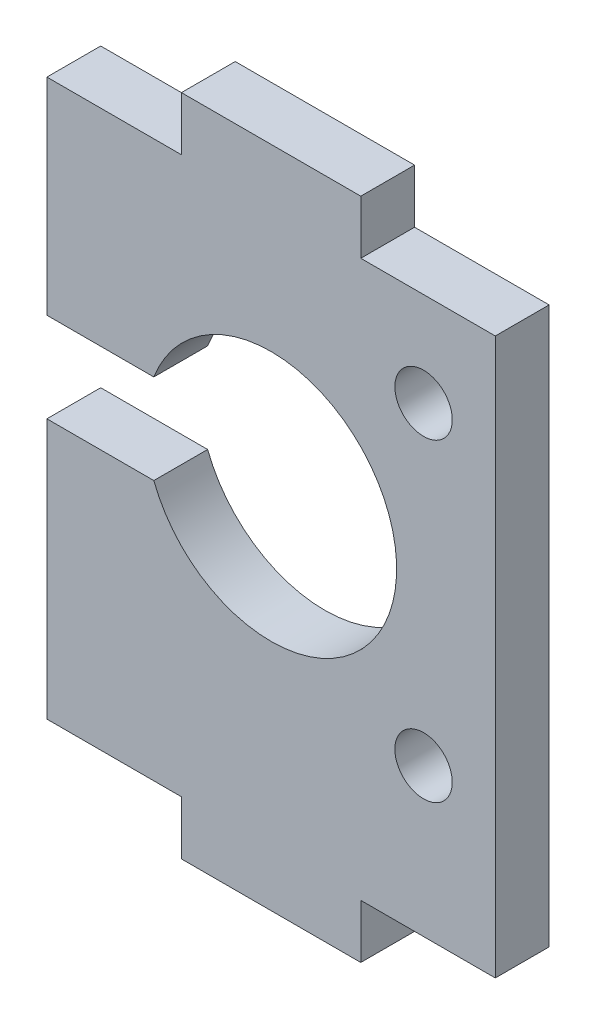
SolidWorks part; units mm, degrees
ref_plane "Front Plane" through (0, 0, 0) normal (0, 0, 1) x (1, 0, 0)
ref_plane "Top Plane" through (0, 0, 0) normal (0, 1, 0) x (1, 0, 0)
ref_plane "Right Plane" through (0, 0, 0) normal (1, 0, 0) x (0, 0, -1)
sketch "Sketch1" plane through (0, 0, 0) normal (0, 0, -1) x (1, 0, 0)
  line L0 (-5, 17) -> (-5, 20)
  line L1 (-12.5, -14) -> (-5, -14)
  line L2 (-12.5, -14) -> (-12.5, -2.5)
  line L3 (-12.5, 17) -> (-5, 17)
  line L4 (12.5, -14) -> (12.5, 17)
  line L5 (-7, 0) -> (7, 0) construction
  line L6 (0, 7) -> (0, -7) construction
  line L7 (-5, 20) -> (5, 20)
  line L8 (5, 20) -> (5, 17)
  line L9 (-12.5, -2.5) -> (-6.5383, -2.5)
  line L13 (5, -14) -> (12.5, -14)
  line L14 (5, 17) -> (12.5, 17)
  line L15 (-5, -14) -> (-5, -17)
  line L16 (-5, -17) -> (5, -17)
  line L17 (5, -17) -> (5, -14)
  line L18 (-12.5, 2.5) -> (-6.5383, 2.5)
  line L19 (-12.5, 2.5) -> (-12.5, 17)
  circle A2 centre (8.5, 8.75) radius 1.6
  arc A6 (-6.5383, -2.5) -> (-6.5383, 2.5) centre (0, 0) ccw
  circle A7 centre (8.5, -8.75) radius 1.6
  dimension "D6" = 8.75
  dimension "D7" = 3.2
  dimension "D9" = 17
  dimension "D5" = 14
  dimension "D2" = 25
  dimension "D3" = 10
  dimension "D4" = 3
  dimension "D8" = 8.5
  dimension "D10" = 3
  dimension "D11" = 14
  dimension "D12" = 10
  dimension "D13" = 12.5
  dimension "D14" = 5
  dimension "D15" = 5
  dimension "D16" = 2.5
extrude "Boss-Extrude1" add sketch "Sketch1" along normal blind 3
